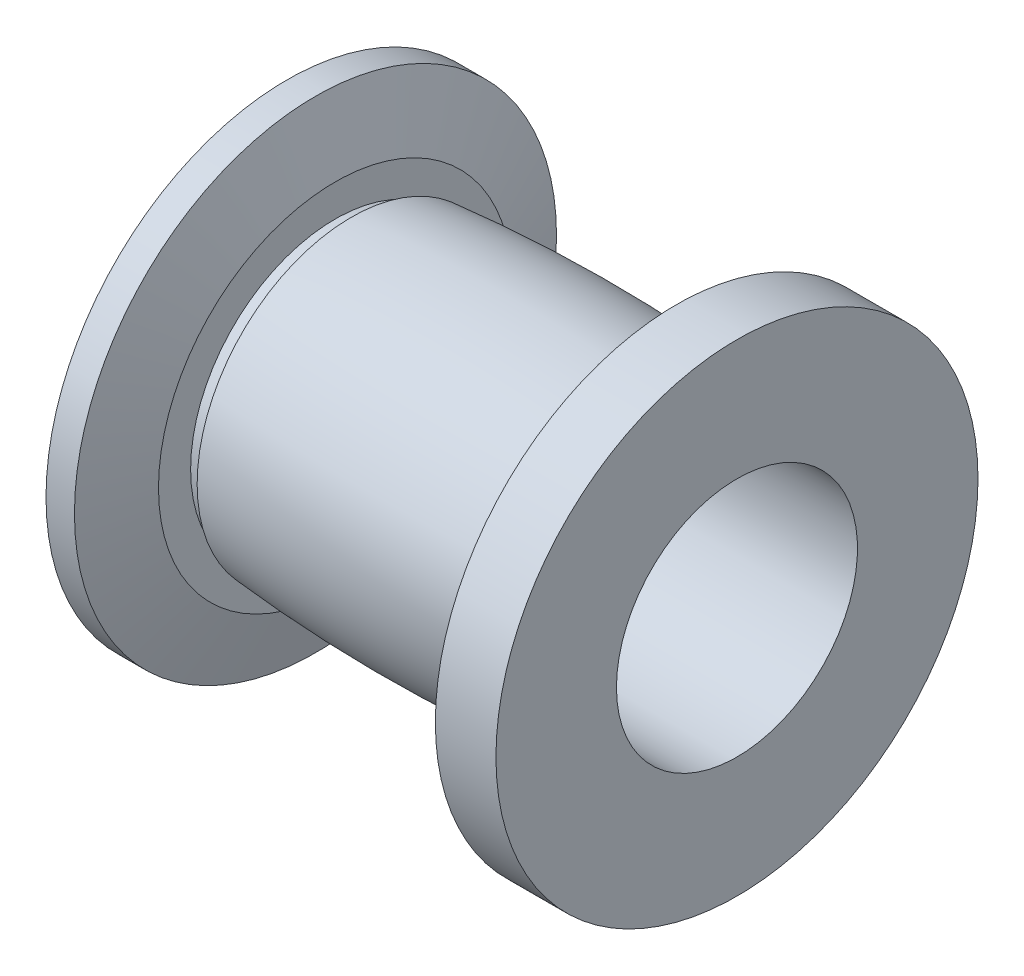
SolidWorks part; units mm, degrees
ref_plane "Front" through (0, 0, 0) normal (0, 0, 1) x (1, 0, 0)
ref_plane "Top" through (0, 0, 0) normal (0, 1, 0) x (1, 0, 0)
ref_plane "Right" through (0, 0, 0) normal (1, 0, 0) x (0, 0, -1)
sketch "Sketch1" plane through (0, 0, 0) normal (0, 0, 1) x (1, 0, 0)
  line L0 (-3.4438, 0) -> (36.6956, 0) construction
  line L1 (0, 0) -> (0, 15)
  line L2 (0, 15) -> (1.77, 15)
  line L3 (1.77, 15) -> (3, 11)
  line L4 (3, 11) -> (3, 9)
  line L5 (3, 9) -> (4, 9)
  line L6 (4, 9) -> (4, 9.5942)
  line L7 (22, 9.5942) -> (22, 9)
  line L8 (22, 9) -> (23, 9)
  line L9 (23, 9) -> (23, 11)
  line L10 (23, 11) -> (24.23, 15)
  line L11 (24.23, 15) -> (28, 15)
  line L12 (28, 15) -> (28, 0)
  line L13 (0, 0) -> (28, 0)
  arc A0 (22, 9.5942) -> (4, 9.5942) centre (13, -90) ccw
  dimension "D4" = 1.77
  dimension "D11" = 100
  dimension "D12" = 20
  dimension "D1" = 30
  dimension "D2" = 22
  dimension "D3" = 18
  dimension "D5" = 3
  dimension "D6" = 4
  dimension "D7" = 22
  dimension "D8" = 23
  dimension "D9" = 24.23
  dimension "D10" = 28
revolve "Revolve1" add sketch "Sketch1" angle 360 about L0
sketch "Sketch2" plane through (0, 0, 0) normal (0, 0, 1) x (1, 0, 0)
  line L0 (-3.3838, 0) -> (30.0568, 0) construction
  line L1 (28, -15) -> (28, 15) construction
  line L2 (0, 0) -> (28, 0)
  line L3 (0, 0) -> (0, 7.5)
  line L4 (0, 7.5) -> (28, 7.5)
  line L5 (28, 0) -> (28, 7.5)
  dimension "D1" = 15
revolve "Cut-Revolve1" cut sketch "Sketch2" angle 360 about L0
